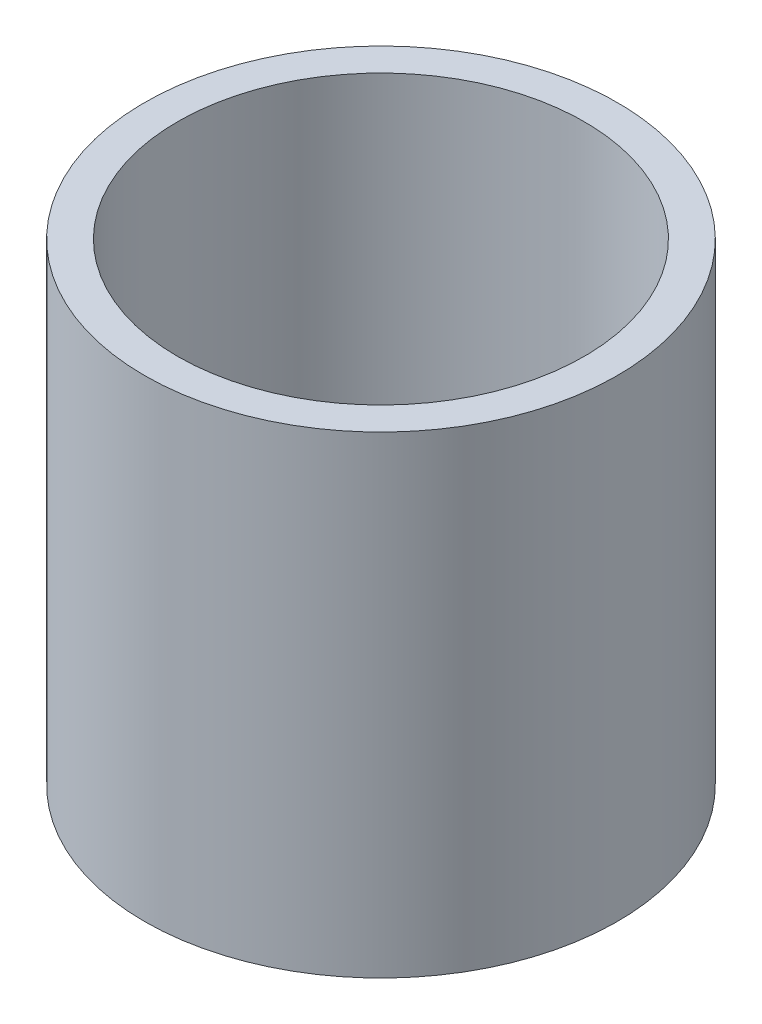
SolidWorks part; units mm, degrees
ref_plane "Front Plane" through (0, 0, 0) normal (0, 0, 1) x (1, 0, 0)
ref_plane "Top Plane" through (0, 0, 0) normal (0, 1, 0) x (1, 0, 0)
ref_plane "Right Plane" through (0, 0, 0) normal (1, 0, 0) x (0, 0, -1)
sketch "Sketch1" plane through (0, 0, 0) normal (0, 1, 0) x (1, 0, 0)
  circle A0 centre (0, 0) radius 50
  dimension "D1" = 100
extrude "Boss-Extrude1" add sketch "Sketch1" along normal blind 100
sketch "Sketch3" plane through (0, 100, 0) normal (0, 1, 0) x (1, 0, 0)
  circle A0 centre (0, 0) radius 43
  circle A1 centre (0, 0) radius 50 construction
  dimension "D1" = 7
extrude "Cut-Extrude2" cut sketch "Sketch3" against normal through all contours A0
